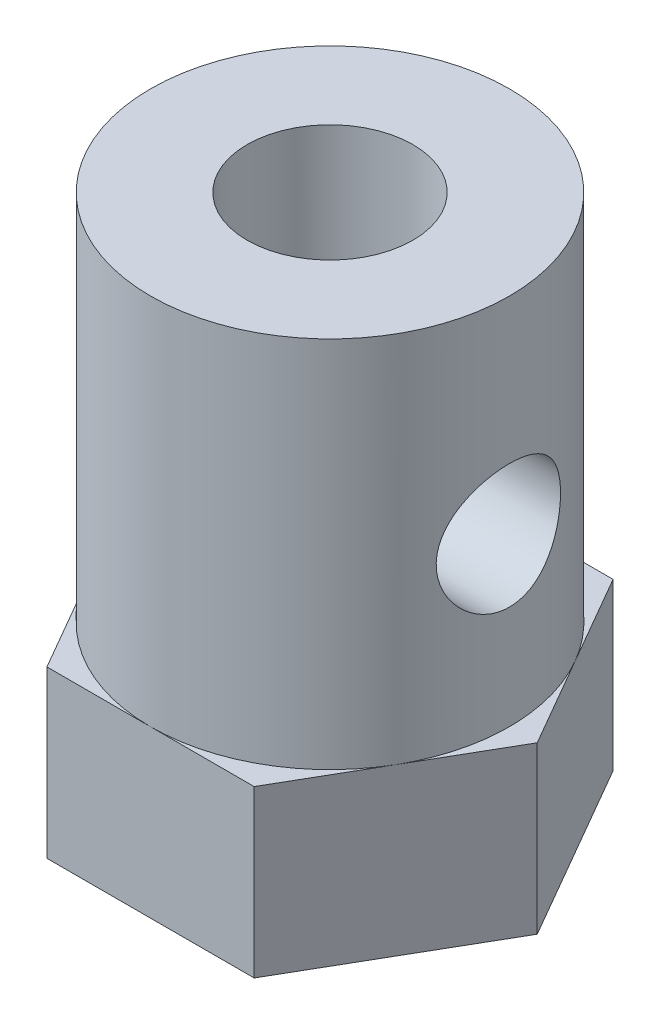
SolidWorks part; units mm, degrees
material "5052-H34"
ref_plane "前视基准面" through (0, 0, 0) normal (0, 0, 1) x (1, 0, 0)
ref_plane "上视基准面" through (0, 0, 0) normal (0, 1, 0) x (1, 0, 0)
ref_plane "右视基准面" through (0, 0, 0) normal (1, 0, 0) x (0, 0, -1)
sketch "草图2" plane through (0, 0, 0) normal (0, 1, 0) x (1, 0, 0)
  line L0 (0, 0) -> (5, 0)
  line L1 (0, 0) -> (2.5, 4.3301)
  line L2 (0, 0) -> (-2.5, 4.3301)
  line L3 (0, 0) -> (-5, 0)
  line L4 (0, 0) -> (-2.5, -4.3301)
  line L5 (0, 0) -> (2.5, -4.3301)
  line L6 (5, 0) -> (2.5, 4.3301)
  line L7 (2.5, 4.3301) -> (-2.5, 4.3301)
  line L8 (-2.5, 4.3301) -> (-5, 0)
  line L9 (-2.5, -4.3301) -> (2.5, -4.3301)
  line L10 (2.5, -4.3301) -> (5, 0)
  line L11 (-2.5, -4.3301) -> (-5, 0)
extrude "凸台-拉伸1" add sketch "草图2" along normal blind 4 contours L2 L8 L3 | L11 L4 L3 | L4 L9 L5 | L5 L10 L0 | L0 L6 L1 | L1 L7 L2
sketch "草图3" plane through (0, 4, 0) normal (0, 1, 0) x (1, 0, 0)
  circle A0 centre (0, 0) radius 2
  circle A1 centre (0, 0) radius 4.3301
extrude "凸台-拉伸2" add sketch "草图3" along normal blind 9
sketch "草图4" plane through (0, 0, 0) normal (0, -1, 0) x (1, 0, 0)
  circle A0 centre (0, 0) radius 1.5
extrude "切除-拉伸1" cut sketch "草图4" against normal blind 15
sketch "草图5" plane through (0, 0, 0) normal (1, 0, 0) x (0, 0, -1)
  circle A0 centre (0, 8) radius 1.5
extrude "切除-拉伸2" cut sketch "草图5" against normal through all both and the other way through all
